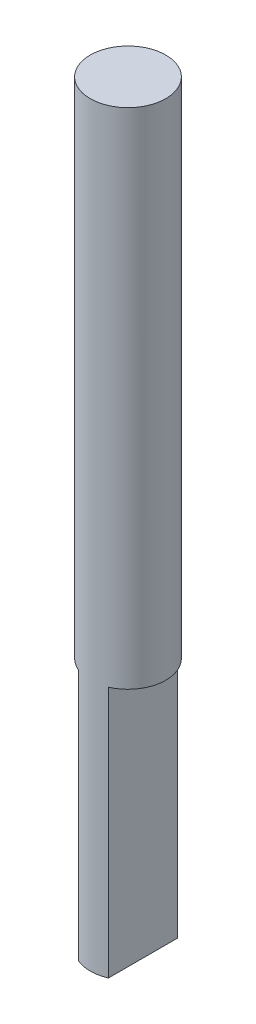
SolidWorks part; units mm, degrees
ref_plane "Front Plane" through (0, 0, 0) normal (0, 0, 1) x (1, 0, 0)
ref_plane "Top Plane" through (0, 0, 0) normal (0, 1, 0) x (1, 0, 0)
ref_plane "Right Plane" through (0, 0, 0) normal (1, 0, 0) x (0, 0, -1)
sketch "Sketch1" plane through (0, 0, 0) normal (0, 1, 0) x (1, 0, 0)
  circle A0 centre (0, 0) radius 0.75
  dimension "D1" = 1.5
extrude "Boss-Extrude1" add sketch "Sketch1" along normal blind 15
sketch "Sketch2" plane through (0, 0, 0) normal (0, -1, 0) x (1, 0, 0)
  line L0 (0, 0.8005) -> (0, -0.8555) construction
  line L1 (-0.3, 0.6874) -> (-0.3, -0.6874)
  line L2 (0.3, 0.6874) -> (0.3, -0.6874)
  circle A0 centre (0, 0) radius 0.75 construction
  arc A1 (-0.3, 0.6874) -> (-0.3, -0.6874) centre (0, 0) ccw
  arc A2 (0.3, -0.6874) -> (0.3, 0.6874) centre (0, 0) ccw
  dimension "D1" = 0.3
  dimension "D2" = 0.3
extrude "Cut-Extrude1" cut sketch "Sketch2" against normal blind 5
